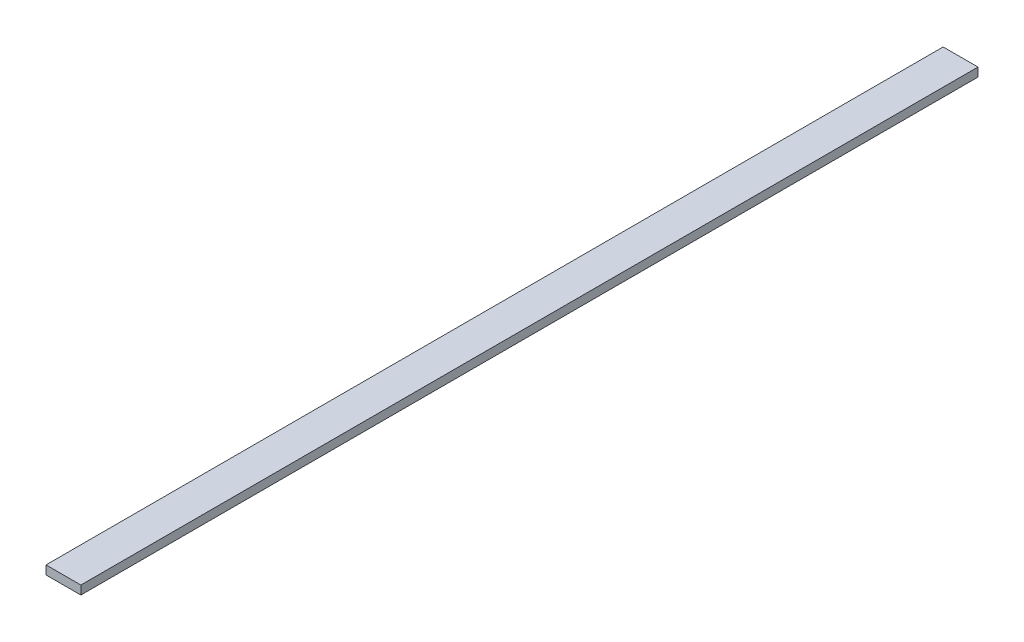
SolidWorks part; units mm, degrees
material "ABS"
ref_plane "Спереди" through (0, 0, 0) normal (0, 0, 1) x (1, 0, 0)
ref_plane "Сверху" through (0, 0, 0) normal (0, 1, 0) x (1, 0, 0)
ref_plane "Справа" through (0, 0, 0) normal (1, 0, 0) x (0, 0, -1)
sketch "Эскиз1" plane through (0, 0, 0) normal (0, 0, 1) x (1, 0, 0)
  line L1 (0, 0) -> (-200, 0)
  line L2 (0, 0) -> (0, 50)
  line L3 (0, 50) -> (-200, 50)
  line L4 (-200, 0) -> (-200, 50)
  dimension "D1" = 200
  dimension "D2" = 50
extrude "Бобышка-Вытянуть1" add sketch "Эскиз1" against normal up to vertex (5150 mm away)
